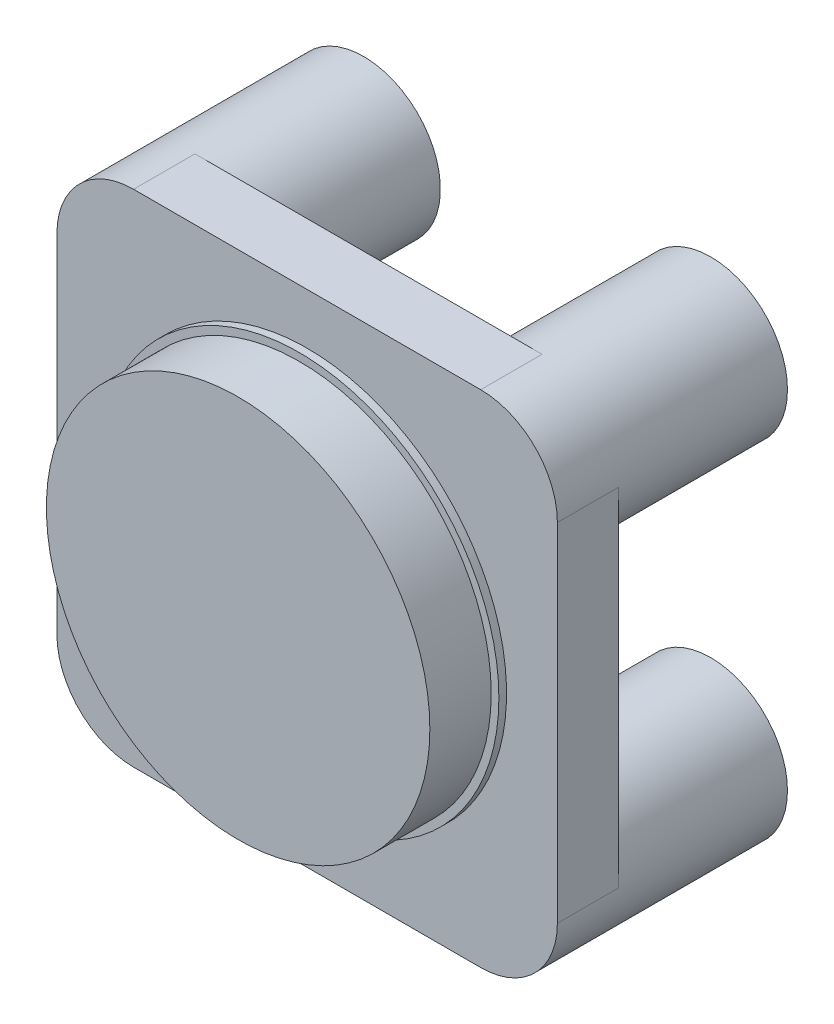
SolidWorks part; units mm, degrees
ref_plane "Front Plane" through (0, 0, 0) normal (0, 0, 1) x (1, 0, 0)
ref_plane "Top Plane" through (0, 0, 0) normal (0, 1, 0) x (1, 0, 0)
ref_plane "Right Plane" through (0, 0, 0) normal (1, 0, 0) x (0, 0, -1)
ref_plane "Output Plane" through (0, 0, 19) normal (0, 0, -1) x (-1, 0, 0)
sketch "CYC Output Sketch" plane through (0, 0, 19) normal (0, 0, 1) x (1, 0, 0)
  line L1 (11.3137, 11.3137) -> (-11.3137, 11.3137) construction
  line L2 (-11.3137, 11.3137) -> (-11.3137, -11.3137) construction
  line L3 (-11.3137, -11.3137) -> (11.3137, -11.3137) construction
  line L4 (11.3137, -11.3137) -> (11.3137, 11.3137) construction
  circle A0 centre (0, 0) radius 16 construction
sketch "Sketch3" plane through (0, 0, 19) normal (0, 0, -1) x (-1, 0, 0)
  circle A0 centre (-11.3137, 11.3137) radius 5
  circle A1 centre (11.3137, 11.3137) radius 5
  circle A2 centre (11.3137, -11.3137) radius 5
  circle A3 centre (-11.3137, -11.3137) radius 5
  dimension "D1" = 10
extrude "Boss-Extrude1" add sketch "Sketch3" along normal blind 15
sketch "Sketch4" plane through (0, 0, 19) normal (0, 0, -1) x (-1, 0, 0)
  line L0 (16.3137, 11.3137) -> (16.3137, -11.3137)
  line L1 (11.3137, -16.3137) -> (-11.3137, -16.3137)
  line L2 (-16.3137, -11.3137) -> (-16.3137, 11.3137)
  line L3 (-11.3137, 16.3137) -> (11.3137, 16.3137)
  circle A0 centre (11.3137, 11.3137) radius 5
  circle A1 centre (-11.3137, 11.3137) radius 5
  circle A2 centre (-11.3137, -11.3137) radius 5
  circle A3 centre (11.3137, -11.3137) radius 5
  circle A4 centre (0, 0) radius 7.575
  dimension "D1" = 15.15
extrude "Boss-Extrude2" add sketch "Sketch4" along normal blind 4 contours A3 L0 A0 L3 A1 L2 A2 L1 A4
sketch "Sketch5" plane through (0, 0, 19) normal (0, 0, 1) x (1, 0, 0)
  circle A0 centre (0, 0) radius 12.5
  dimension "D1" = 25
extrude "Boss-Extrude3" add sketch "Sketch5" along normal blind 4.5
sketch "Sketch6" plane through (0, 0, 19) normal (0, 0, 1) x (1, 0, 0)
  circle A0 centre (0, 0) radius 12.5
  circle A1 centre (0, 0) radius 13
  dimension "D1" = 26
  dimension "D2" = 25
extrude "Boss-Extrude4" add sketch "Sketch6" along normal blind 0.5
equation "\"RingPinShaft\"= 5"
equation "\"CenterBearingOut\"=32"
equation "\"RingPostIn\"=5"
equation "\"CamBearingOut\"=15.15"
equation "\"DiskOutputShaft\"=10"
equation "\"CenterShaft\"=25"
equation "\"Eccentricity\"=2"
equation "\"CycCamShaft\"=10"
equation "\"D1@Sketch4\"=\"CamBearingOut\""
equation "\"D1@Sketch5\"=\"CenterShaft\""
equation "\"D1@Sketch6\"=\"CenterShaft\"+1"
equation "\"D2@Sketch6\"=\"CenterShaft\""
